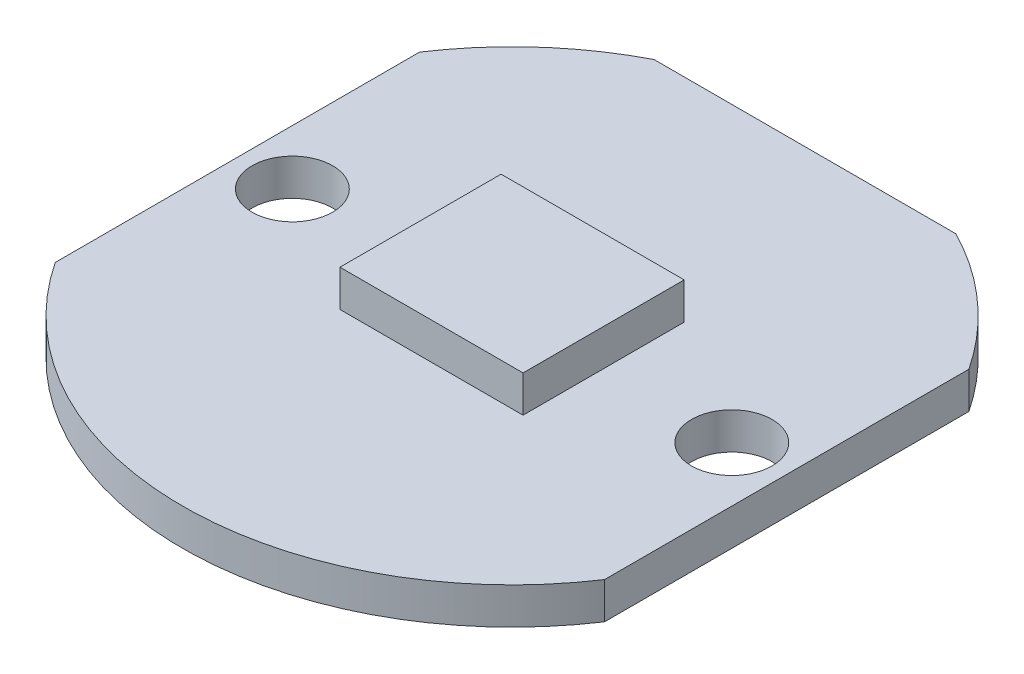
SolidWorks part; units mm, degrees
ref_plane "Front" through (0, 0, 0) normal (0, 0, 1) x (1, 0, 0)
ref_plane "Top" through (0, 0, 0) normal (0, 1, 0) x (1, 0, 0)
ref_plane "Right" through (0, 0, 0) normal (1, 0, 0) x (0, 0, -1)
sketch "Эскиз1" plane through (0, 0, 0) normal (0, 1, 0) x (1, 0, 0)
  line L0 (0, 0) -> (0, 24.3532) construction
  line L1 (0, 0) -> (-41.2832, 0) construction
  line L2 (-7.5, 8) -> (7.5, 8)
  line L3 (-7.5, 8) -> (-7.5, -4.9749)
  line L4 (7.5, 8) -> (7.5, -4.9749)
  circle A0 centre (0, 0) radius 9
  circle A1 centre (0, 0) radius 6 construction
  circle A2 centre (-6, 0) radius 1.1
  circle A4 centre (6, 0) radius 1.1
  point P9 (0, -9)
  dimension "D1" = 18
  dimension "D5" = 2.2
  dimension "D2" = 17
  dimension "D3" = 15
  dimension "D4" = 7.5
extrude "Бобышка-Вытянуть1" add sketch "Эскиз1" along normal blind 1 contours L4 A0 L2 L3 A4 A2
sketch "Эскиз3" plane through (0, 0, 0) normal (0, 1, 0) x (1, 0, 0)
  line L1 (2.5, -2.2) -> (-2.5, -2.2)
  line L2 (2.5, -2.2) -> (2.5, 2.2)
  line L3 (2.5, 2.2) -> (-2.5, 2.2)
  line L4 (-2.5, -2.2) -> (-2.5, 2.2)
  line L5 (2.5, -2.2) -> (-2.5, 2.2) construction
  line L6 (2.5, 2.2) -> (-2.5, -2.2) construction
  point P0 (0, 0)
  dimension "D1" = 5
  dimension "D2" = 4.4
extrude "Бобышка-Вытянуть2" add sketch "Эскиз3" along normal blind 1 from offset 1 separate body
